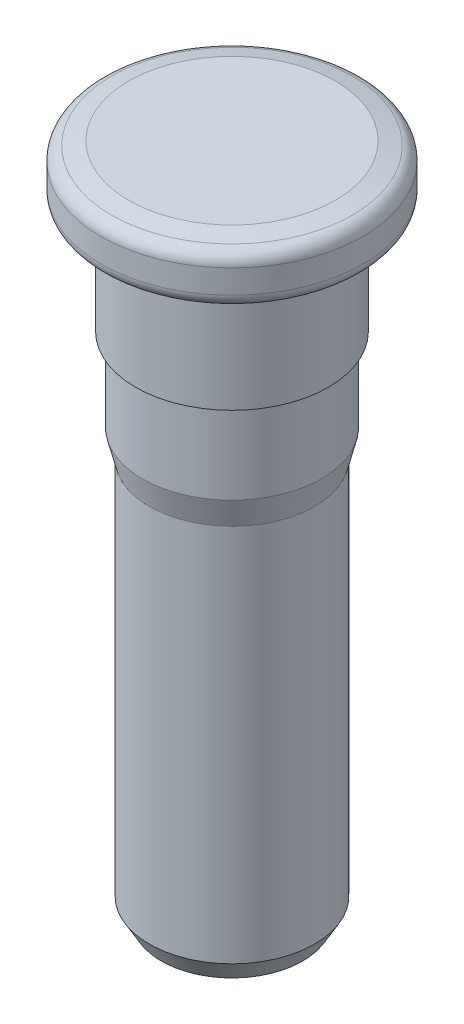
SolidWorks part; units mm, degrees
ref_plane "Plano frontal" through (0, 0, 0) normal (0, 0, 1) x (1, 0, 0)
ref_plane "Plano superior" through (0, 0, 0) normal (0, 1, 0) x (1, 0, 0)
ref_plane "Plano direito" through (0, 0, 0) normal (1, 0, 0) x (0, 0, -1)
sketch "Esboço1" plane through (0, 0, 0) normal (0, 0, 1) x (1, 0, 0)
  line L0 (0, -66.8262) -> (0, 59.4143) construction
  line L1 (0, 44.337) -> (7.5, 44.337)
  line L2 (7.5, 44.337) -> (9.5, 43.837)
  line L3 (9.5, 43.837) -> (9.5, 40.337)
  line L4 (9.5, 40.337) -> (7, 40.337)
  line L5 (7, 40.337) -> (7, 32.337)
  line L6 (7, 32.337) -> (6.5, 32.337)
  line L7 (6.5, 32.337) -> (6.5, 26.337)
  line L8 (6.5, 26.337) -> (6, 24.337)
  line L9 (6, 24.337) -> (6, -4.663)
  line L10 (6, -4.663) -> (0, -4.663)
  line L11 (0, 44.337) -> (0, -4.663)
  dimension "D1" = 6
  dimension "D2" = 9.5
  dimension "D3" = 6.5
  dimension "D4" = 7
  dimension "D5" = 7.5
  dimension "D6" = 0.5
  dimension "D7" = 4
  dimension "D8" = 12
  dimension "D9" = 20
  dimension "D10" = 45
revolve "Revolução1" add sketch "Esboço1" angle 360 about L0
fillet "Filete1" radius 1 1 edges at (0, 43.837, -9.5)
fillet "Filete2" radius 1 1 edges at (0, 40.337, -9.5)
chamfer "Chanfro1" distance 1.5 angle 30 1 edges at (0, -4.663, -6)
